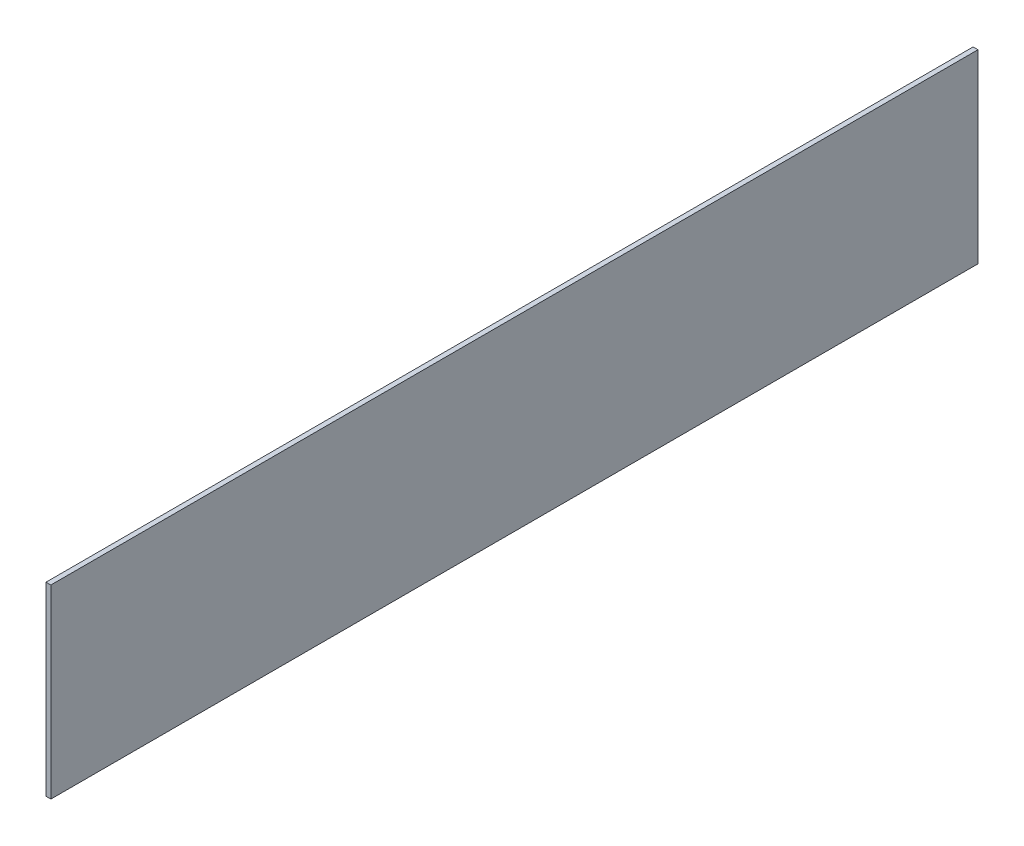
SolidWorks part; units mm, degrees
ref_plane "Front Plane" through (0, 0, 0) normal (0, 0, 1) x (1, 0, 0)
ref_plane "Top Plane" through (0, 0, 0) normal (0, 1, 0) x (1, 0, 0)
ref_plane "Right Plane" through (0, 0, 0) normal (1, 0, 0) x (0, 0, -1)
sketch "Sketch1" plane through (0, 0, 0) normal (1, 0, 0) x (0, 0, -1)
  line L1 (-190.5, 38.1) -> (190.5, 38.1)
  line L2 (-190.5, 38.1) -> (-190.5, -38.1)
  line L3 (-190.5, -38.1) -> (190.5, -38.1)
  line L4 (190.5, 38.1) -> (190.5, -38.1)
  line L5 (-190.5, 38.1) -> (190.5, -38.1) construction
  line L6 (-190.5, -38.1) -> (190.5, 38.1) construction
  point P0 (0, 0)
extrude "Boss-Extrude1" add sketch "Sketch1" along normal blind 2
